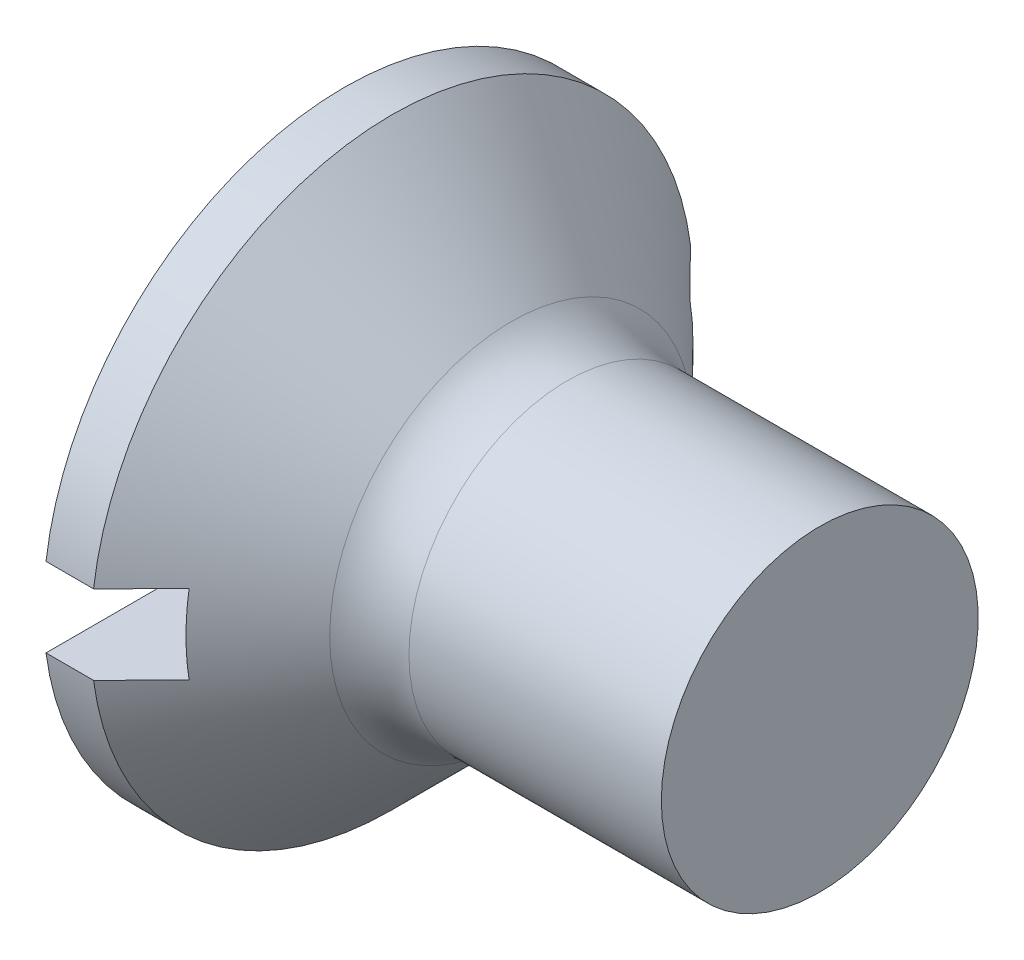
SolidWorks part; units mm, degrees
revolve "Base-Revolve" add sketch "BodySke" angle 360 about L5
sketch "BodySke" plane through (0, 0, 0) normal (0, 0, 1) x (1, 0, 0)
  line L0 (0, 0) -> (0, 1.9)
  line L1 (0, 1.9) -> (0.3, 1.9)
  line L2 (1.2, 1) -> (3, 1)
  line L3 (3, 1) -> (3, 0)
  line L4 (3, 0) -> (0, 0)
  line L5 (-6.35, 0) -> (82.55, 0) construction
  line L6 (1.2, -1) -> (3, -1) construction
  line L7 (0.3, -1.9) -> (1.2, -1) construction
  line L8 (0.3, 1.9) -> (1.2, 1)
  line L9 (0, -1.9) -> (0.3, -1.9) construction
  line L10 (1.6, 2.5875) -> (1.6, -6.9375) construction
  line L11 (0, 6.35) -> (0, -3.175) construction
  dimension "Diameter" = 2
  dimension "Length" = 3
  dimension "Head_ht" = 1.2
  dimension "Head_dia" = 3.8
  dimension "Head_ang" = 90
  dimension "D6" = 0.3
  dimension "Advance" = 0.4
  dimension "Thread_nom" = 3
cosmetic thread "ThreadCosmetic" [suppressed] parameters "Thread_length"=1.4, "Thread_minor"=1.548
extrude "Slot" cut sketch "Sketch2" against normal blind 0.6
sketch "Sketch2" plane through (0, 0, 0) normal (-1, 0, 0) x (0, 0, 1)
  line L0 (-1.9, -0.25) -> (1.9, -0.25)
  line L1 (-1.9, -0.25) -> (-1.9, 0.25)
  line L2 (1.9, 0.25) -> (-1.9, 0.25)
  line L3 (1.9, 0.25) -> (1.9, -0.25)
  dimension "Slot_width" = 0.5
  dimension "D1" = 0.25
  dimension "D2" = 3.8
  dimension "D3" = 1.9
ref_plane "Plane1" through (0, 0, 0) normal (0, 0, 1) x (1, 0, 0)
ref_plane "Plane2" through (0, 0, 0) normal (0, 1, 0) x (1, 0, 0)
ref_plane "Plane3" through (0, 0, 0) normal (1, 0, 0) x (0, 0, -1)
fillet "Fillet1" radius 0.5 1 edges at (1.2, 0, 1)
sketch "ThdSchSke" plane through (0, 0, 0) normal (0, 0, 1) x (1, 0, 0)
  line L0 (1.6, -0.774) -> (1.4418, -1)
  line L1 (1.6, -0.774) -> (1.7582, -1)
  line L2 (1.7582, -1) -> (1.7582, -1.25)
  line L3 (-3.175, 0) -> (5.1513, 0) construction
  line L5 (1.7582, -1.25) -> (1.4418, -1.25)
  line L6 (1.4418, -1.25) -> (1.4418, -1)
  line L7 (0, 1.9) -> (0, 0.25) construction
  dimension "Diameter" = 2
  dimension "Thread_minor" = 1.548
  dimension "Start" = 1.6
revolve "ThreadSchematic" [suppressed] cut sketch "ThdSchSke" angle 360 about L3
pattern_linear "ThdSchPat" [suppressed]
equation "\"D1@Sketch2\" = \"Slot_width@Sketch2\" / 2"
equation "\"D2@Sketch2\" = \"Head_dia@BodySke\""
equation "\"D3@Sketch2\" = \"D2@Sketch2\" / 2"
equation "\"Thread_length@ThreadCosmetic\" = ((sgn( (\"Length@BodySke\" - \"Advance@BodySke\" * 1.0 - \"Head_ht@BodySke\" ) - \"Thread_nom@BodySke\" )-1)*( (\"Length@BodySke\" - \"Advance@BodySke\" * 1.0 - \"Head_ht@BodySke\" ) - \"Thread_nom@BodySke\" ))/-2+ \"Thread_nom@BodySke\""
equation "\"Thread_minor@ThdSchSke\" = \"Thread_minor@ThreadCosmetic\""
equation "\"Diameter@ThdSchSke\" = \"Diameter@BodySke\""
equation "\"Overcut@ThdSchSke\" = \"Diameter@BodySke\" * 1.25"
equation "\"Start@ThdSchSke\" = 0.000001 + \"Length@BodySke\" - \"Thread_length@ThreadCosmetic\"  '---Countersunk---"
equation "\"Num_threads@ThdSchPat\" = int( \"Thread_length@ThreadCosmetic\" / \"Advance@BodySke\" + 0.999 )  + 1"
equation "\"Advance@ThdSchPat\" = \"Thread_length@ThreadCosmetic\" /  (\"Num_threads@ThdSchPat\" - 1) 'relax it"
